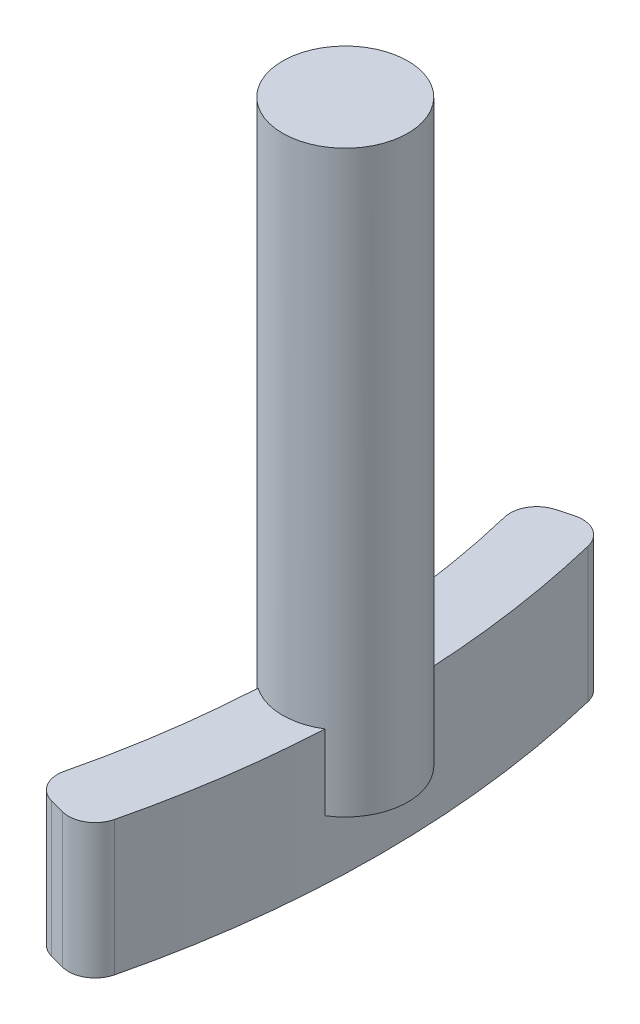
SolidWorks part; units mm, degrees
material "ABS"
ref_plane "Front Plane" through (0, 0, 0) normal (0, 0, 1) x (1, 0, 0)
ref_plane "Top Plane" through (0, 0, 0) normal (0, 1, 0) x (1, 0, 0)
ref_plane "Right Plane" through (0, 0, 0) normal (1, 0, 0) x (0, 0, -1)
sketch "Эскиз1" plane through (0, 0, 0) normal (0, 1, 0) x (1, 0, 0)
  line L12 (-0.9012, -8.0529) -> (-0.4181, -8.1824)
  line L13 (-0.9012, 8.0529) -> (-0.4181, 8.1824)
  arc A36 (0.6279, -7.5615) -> (-0.4181, -8.1824) centre (-0.1981, -7.3613) cw
  arc A37 (0.6279, -7.5615) -> (0.6279, 7.5615) centre (-30.5687, 0) ccw
  arc A38 (-0.4181, 8.1824) -> (0.6279, 7.5615) centre (-0.1981, 7.3613) cw
  arc A39 (-0.9012, 8.0529) -> (-1.5074, 7.032) centre (-0.6813, 7.2319) ccw
  arc A40 (-1.5074, -7.032) -> (-1.5074, 7.032) centre (-30.5687, 0) ccw
  arc A41 (-0.9012, -8.0529) -> (-1.5074, -7.032) centre (-0.6813, -7.2319) cw
extrude "Бобышка-Вытянуть1" add sketch "Эскиз1" along normal blind 4.3
ref_plane "Плоскость1" through (0, 1.9, 0) normal (0, 1, 0) x (1, 0, 0)
sketch "Эскиз2" plane through (0, 1.9, 0) normal (0, 1, 0) x (1, 0, 0)
  circle A2 centre (0.4313, 0) radius 2
  dimension "D1" = 4
extrude "Бобышка-Вытянуть2" add sketch "Эскиз2" along normal blind 18.5
